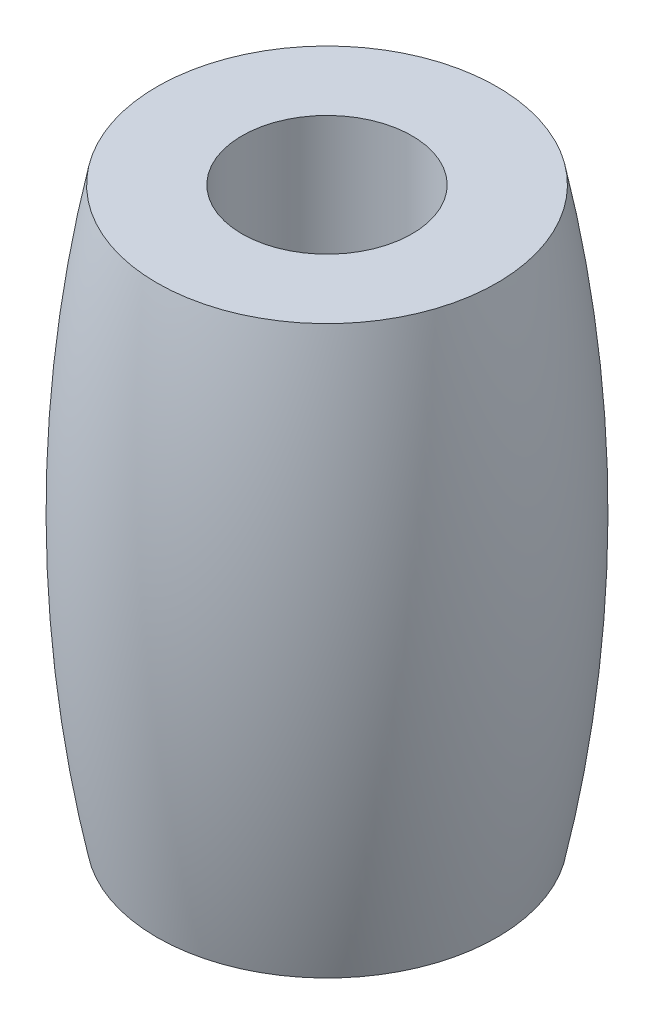
SolidWorks part; units mm, degrees
ref_plane "Front Plane" through (0, 0, 0) normal (0, 0, 1) x (1, 0, 0)
ref_plane "Top Plane" through (0, 0, 0) normal (0, 1, 0) x (1, 0, 0)
ref_plane "Right Plane" through (0, 0, 0) normal (1, 0, 0) x (0, 0, -1)
sketch "Sketch2" plane through (0, 0, 0) normal (0, 0, 1) x (1, 0, 0)
  line L0 (0, 0) -> (3, 0)
  line L1 (3, 10) -> (0, 10)
  line L2 (0, 10) -> (0, 0)
  arc A0 (3, 0) -> (3, 10) centre (-21.4949, 5) ccw
revolve "Revolve1" add sketch "Sketch2" angle 360 about L2
sketch "Sketch3" plane through (0, 10, 0) normal (0, 1, 0) x (1, 0, 0)
  circle A0 centre (0, 0) radius 1.5
extrude "Cut-Extrude1" cut sketch "Sketch3" against normal through all
